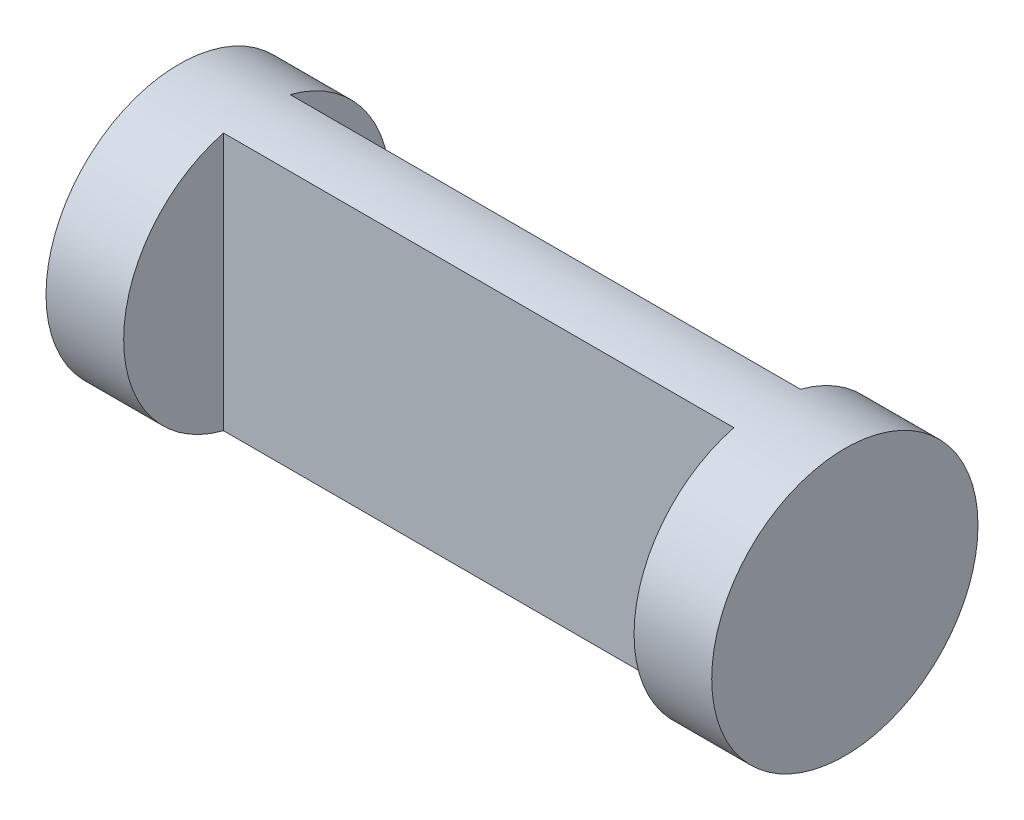
SolidWorks part; units mm, degrees
ref_plane "Спереди" through (0, 0, 0) normal (0, 0, 1) x (1, 0, 0)
ref_plane "Сверху" through (0, 0, 0) normal (0, 1, 0) x (1, 0, 0)
ref_plane "Справа" through (0, 0, 0) normal (1, 0, 0) x (0, 0, -1)
sketch "Эскиз1" plane through (0, 0, 0) normal (0, 0, 1) x (1, 0, 0)
  line L0 (0, 0) -> (60, 0)
  line L1 (60, 0) -> (60, 12)
  line L2 (60, 12) -> (0, 12)
  line L6 (0, 12) -> (0, 0)
  dimension "D1" = 12
  dimension "D2" = 60
revolve "Повернуть1" add sketch "Эскиз1" angle 360 about L0
ref_plane "Плоскость1" through (30, 0, 0) normal (-1, 0, 0) x (0, 0, 1)
sketch "Эскиз2" plane through (30, 0, 0) normal (-1, 0, 0) x (0, 0, 1)
  line L0 (3, 11.619) -> (3, -11.619)
  circle A0 centre (0, 0) radius 12 construction
  circle A1 centre (0, 0) radius 12
  dimension "D1" = 3
extrude "Вырез-Вытянуть2" cut sketch "Эскиз2" against normal offset from surface 7 and the other way offset from surface (23 mm away) 7 contours L0 A1
mirror "Зеркальное отражение1" about plane through (0, 0, 0) normal (0, 0, 1) of "Вырез-Вытянуть2"
